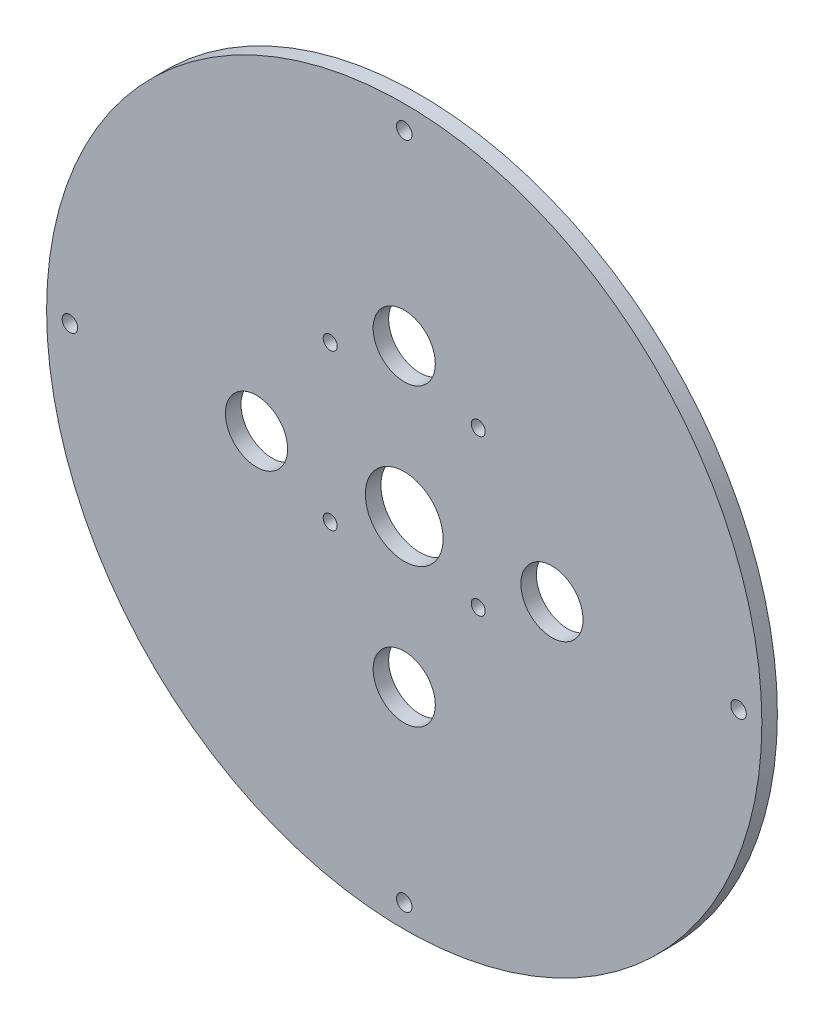
SolidWorks part; units mm, degrees
ref_plane "Front Plane" through (0, 0, 0) normal (0, 0, 1) x (1, 0, 0)
ref_plane "Top Plane" through (0, 0, 0) normal (0, 1, 0) x (1, 0, 0)
ref_plane "Right Plane" through (0, 0, 0) normal (1, 0, 0) x (0, 0, -1)
sketch "Sketch1" plane through (0, 0, 0) normal (0, 0, 1) x (1, 0, 0)
  line L0 (0, -1.0939) -> (0, 111.1446) construction
  line L1 (-27.2427, 14.732) -> (30.45, 14.732) construction
  circle A0 centre (0, 0) radius 146.05
  circle A1 centre (0, 136.525) radius 3.175
  circle A2 centre (136.525, 0) radius 3.175
  circle A3 centre (0, -136.525) radius 3.175
  circle A4 centre (-136.525, 0) radius 3.175
  circle A5 centre (-30.226, 46.482) radius 2.8575
  circle A6 centre (30.226, 46.482) radius 2.8575
  circle A7 centre (30.226, -17.018) radius 2.8575
  circle A8 centre (-30.226, -17.018) radius 2.8575
  circle A9 centre (0, 0) radius 15.875
  circle A10 centre (0, 60.325) radius 12.7
  circle A11 centre (60.325, 0) radius 12.7
  circle A12 centre (0, -60.325) radius 12.7
  circle A13 centre (-60.325, 0) radius 12.7
  point P14 (0, 0)
  point P16 (0, 14.732)
  point P37 (0, 0)
  dimension "D2" = 6.35
  dimension "D4" = 292.1
  dimension "D6" = 5.715
  dimension "D9" = 31.75
  dimension "D10" = 25.4
  dimension "D3" = 136.525
  dimension "D5" = 14.732
  dimension "D7" = 31.75
  dimension "D8" = 30.226
  dimension "D11" = 60.325
  dimension "D1" = 4
  dimension "D12" = 4
extrude "Boss-Extrude1" add sketch "Sketch1" along normal blind 6.35
